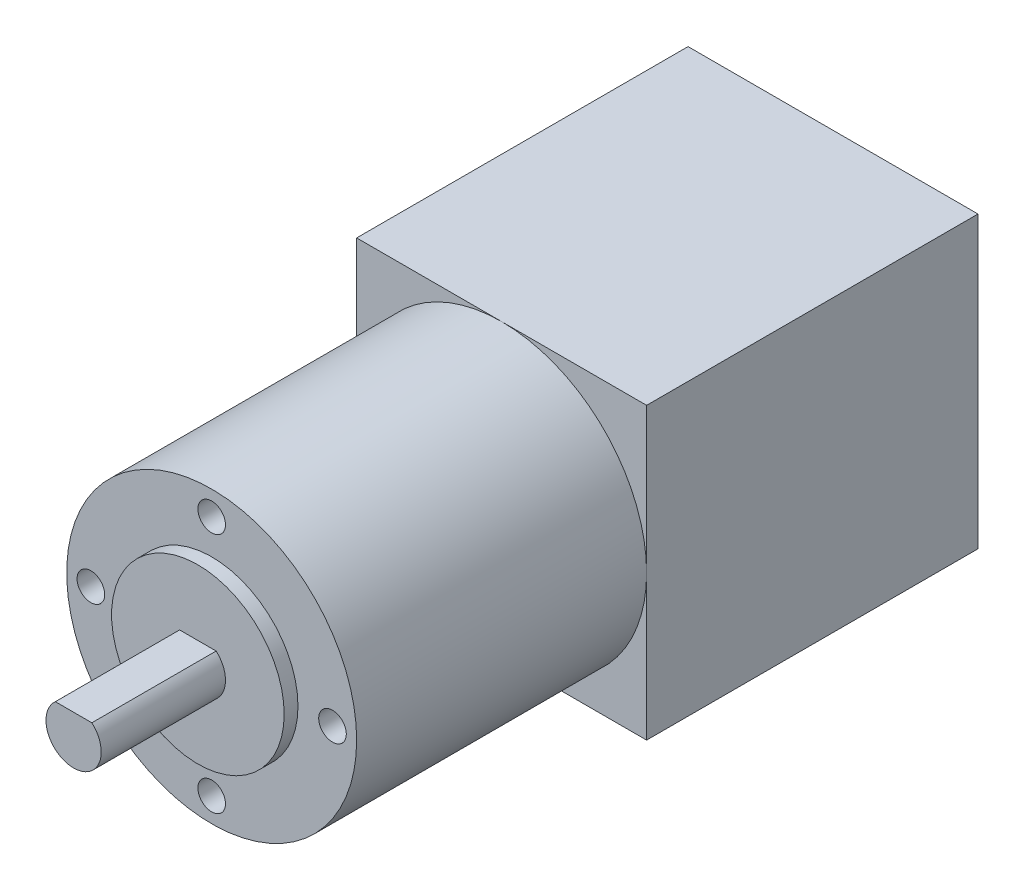
SolidWorks part; units mm, degrees
ref_plane "前视基准面" through (0, 0, 0) normal (0, 0, 1) x (1, 0, 0)
ref_plane "上视基准面" through (0, 0, 0) normal (0, 1, 0) x (1, 0, 0)
ref_plane "右视基准面" through (0, 0, 0) normal (1, 0, 0) x (0, 0, -1)
sketch "草图1" plane through (0, 0, 0) normal (0, 0, 1) x (1, 0, 0)
  line L1 (-21, 21) -> (21, 21)
  line L2 (-21, 21) -> (-21, -21)
  line L3 (-21, -21) -> (21, -21)
  line L4 (21, 21) -> (21, -21)
  line L5 (-21, 21) -> (21, -21) construction
  line L6 (-21, -21) -> (21, 21) construction
  point P0 (0, 0)
  dimension "D1" = 42
extrude "凸台-拉伸1" add sketch "草图1" along normal blind 48
sketch "草图2" plane through (0, 0, 48) normal (0, 0, 1) x (1, 0, 0)
  circle A0 centre (0, 0) radius 21
extrude "凸台-拉伸2" add sketch "草图2" along normal blind 42
sketch "草图3" plane through (0, 0, 90) normal (0, 0, 1) x (1, 0, 0)
  circle A0 centre (0, 0) radius 12.5
extrude "凸台-拉伸3" add sketch "草图3" along normal blind 2
sketch "草图4" plane through (0, 0, 92) normal (0, 0, 1) x (1, 0, 0)
  line L1 (-2.6458, 3) -> (2.6458, 3)
  circle A0 centre (0, 0) radius 4 construction
  arc A1 (-2.6458, 3) -> (2.6458, 3) centre (0, 0) ccw
  dimension "D1" = 8
  dimension "D2" = 3
extrude "凸台-拉伸4" add sketch "草图4" along normal blind 18
sketch "草图5" plane through (0, 0, 90) normal (0, 0, 1) x (1, 0, 0)
  circle A0 centre (0, 0) radius 17.5 construction
  circle A1 centre (0, -17.5) radius 2
  circle A2 centre (-17.5, 0) radius 2
  circle A3 centre (0, 17.5) radius 2
  circle A4 centre (17.5, 0) radius 2
  dimension "D1" = 4
extrude "切除-拉伸1" cut sketch "草图5" against normal blind 4
